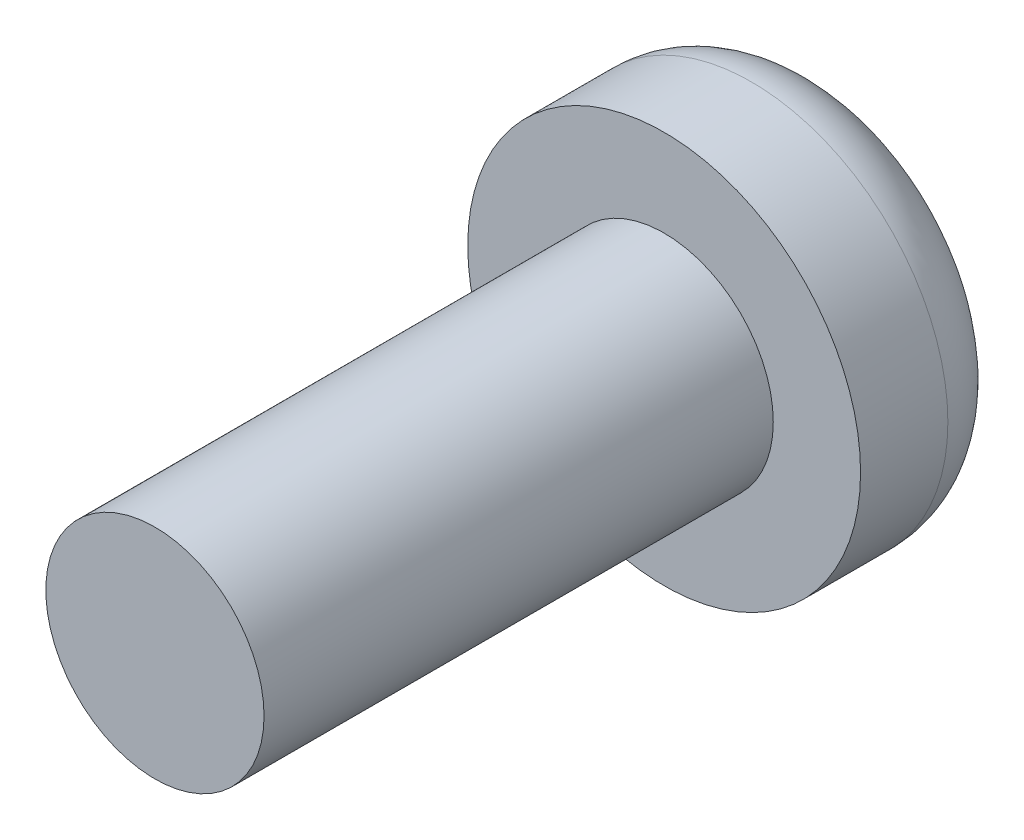
SolidWorks part; units mm, degrees
ref_plane "前视基准面" through (0, 0, 0) normal (0, 0, 1) x (1, 0, 0)
ref_plane "上视基准面" through (0, 0, 0) normal (0, 1, 0) x (1, 0, 0)
ref_plane "右视基准面" through (0, 0, 0) normal (1, 0, 0) x (0, 0, -1)
sketch "草图1" plane through (0, 0, 0) normal (0, 0, 1) x (1, 0, 0)
  circle A0 centre (0, 0) radius 1.5
extrude "凸台-拉伸1" add sketch "草图1" along normal blind 7
sketch "草图2" plane through (0, 0, 0) normal (0, 0, -1) x (-1, 0, 0)
  circle A0 centre (0, 0) radius 2.7
extrude "凸台-拉伸2" add sketch "草图2" along normal blind 2.2
fillet "圆角1" radius 1 1 edges at (-2.7, 0, -2.2)
